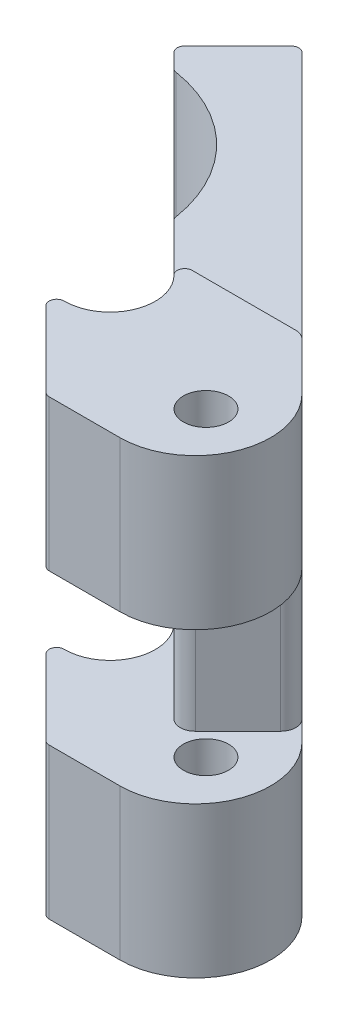
SolidWorks part; units mm, degrees
ref_plane "前视基准面" through (0, 0, 0) normal (0, 0, 1) x (1, 0, 0)
ref_plane "上视基准面" through (0, 0, 0) normal (0, 1, 0) x (1, 0, 0)
ref_plane "右视基准面" through (0, 0, 0) normal (1, 0, 0) x (0, 0, -1)
sketch "Sketch1" plane through (0, 0, 0) normal (0, 1, 0) x (1, 0, 0)
  line L0 (0, 0) -> (23.163, -23.163)
  line L1 (21.0416, -28.2843) -> (0, -28.2843)
  line L2 (0, 3.0516) -> (0, -30.2047) construction
  line L3 (4.2426, 4.2426) -> (34.234, -25.7487)
  line L4 (30.6985, -34.2843) -> (0, -34.2843)
  line L5 (0, 0) -> (4.2426, 4.2426)
  line L6 (0, -28.2843) -> (0, -34.2843)
  line L7 (4.2426, 4.2426) -> (42.7696, -34.2843) construction
  line L8 (42.7696, -34.2843) -> (0, -34.2843) construction
  line L9 (0, 0) -> (28.2843, -28.2843) construction
  line L10 (28.2843, -28.2843) -> (0, -28.2843) construction
  line L11 (21.0416, -25.2843) -> (30.6985, -29.2843) construction
  line L12 (30.6985, -29.2843) -> (46.0994, -35.6635) construction
  arc A0 (34.234, -25.7487) -> (30.6985, -34.2843) centre (30.6985, -29.2843) cw
  arc A1 (23.163, -23.163) -> (21.0416, -28.2843) centre (21.0416, -25.2843) cw
  circle A2 centre (31.9056, -29.7843) radius 1.6
  point P15 (28.2843, -28.2843)
  dimension "D4" = 5
  dimension "D5" = 3
  dimension "D6" = 3.2
  dimension "D1" = 40
  dimension "D2" = 45
  dimension "D7" = 4.5
  dimension "D3" = 6
extrude "Boss-Extrude1" add sketch "Sketch1" along normal blind 10
sketch "Sketch2" plane through (0, 10, 0) normal (0, 1, 0) x (1, 0, 0)
  line L1 (1.4142, -1.4142) -> (9.8995, -9.8995)
  line L2 (4.2426, 4.2426) -> (0, 0) construction
  line L3 (0, 0) -> (23.163, -23.163) construction
  line L5 (0, -28.2843) -> (0, -34.2843)
  line L11 (19.799, -28.2843) -> (25.799, -34.2843)
  line L12 (0, -28.2843) -> (19.799, -28.2843)
  line L13 (21.0416, -28.2843) -> (0, -28.2843) construction
  line L14 (0, -34.2843) -> (25.799, -34.2843)
  line L15 (0, -34.2843) -> (30.6985, -34.2843) construction
  line L16 (34.234, -25.7487) -> (4.2426, 4.2426) construction
  arc A1 (9.8995, -9.8995) -> (1.4142, -1.4142) centre (0, -11.3137) ccw
  dimension "D1" = 8
  dimension "D4" = 10
  dimension "D2" = 12
  dimension "D3" = 8
extrude "Cut-Extrude1" cut sketch "Sketch2" against normal through all
fillet "Fillet1" radius 0.5 6 edges at (25.799, 5, 34.2843) (19.799, 5, 28.2843) (1.4142, 5, 1.4142) (9.8995, 5, 9.8995) (0, 5, 0) (4.2426, 5, -4.2426)
sketch "Sketch3" plane through (0, 10, 0) normal (0, 1, 0) x (1, 0, 0)
  line L0 (20.6525, -29.1378) -> (25.6525, -34.1378)
  line L1 (26.0061, -34.2843) -> (30.6985, -34.2843)
  line L2 (22.2843, -22.2843) -> (30.3553, -22.2843)
  line L3 (31.0624, -22.5772) -> (34.234, -25.7487)
  line L4 (34.234, -25.7487) -> (4.5962, 3.8891) construction
  line L5 (22.2843, -22.2843) -> (23.163, -23.163)
  line L6 (10.0158, -10.0158) -> (23.163, -23.163) construction
  line L7 (21.0061, -28.2843) -> (21.0416, -28.2843)
  circle A2 centre (31.9056, -29.7843) radius 1.5
  arc A3 (21.0061, -28.2843) -> (20.6525, -29.1378) centre (21.0061, -28.7843) ccw
  arc A4 (25.6525, -34.1378) -> (26.0061, -34.2843) centre (26.0061, -33.7843) ccw
  arc A6 (30.3553, -22.2843) -> (31.0624, -22.5772) centre (30.3553, -23.2843) cw
  arc A7 (23.163, -23.163) -> (21.0416, -28.2843) centre (21.0416, -25.2843) cw
  arc A8 (21.0416, -28.2843) -> (23.163, -23.163) centre (21.0416, -25.2843) ccw construction
  arc A9 (30.6985, -34.2843) -> (34.234, -25.7487) centre (30.6985, -29.2843) ccw
  arc A10 (30.6985, -34.2843) -> (34.234, -25.7487) centre (30.6985, -29.2843) ccw construction
  dimension "D1" = 3
  dimension "D2" = 1.2426
  dimension "D3" = 1
  dimension "D4" = 1
  dimension "D5" = 1
extrude "Boss-Extrude2" add sketch "Sketch3" along normal blind 10 and the other way blind 20
sketch "Sketch4" plane through (0, 0, 0) normal (-0.7071, 0, 0.7071) x (0.7071, 0, 0.7071)
  line L0 (31.5147, 10) -> (41.5147, 10)
  line L1 (41.5147, 10) -> (41.5147, 0)
  line L2 (41.5147, 0) -> (31.5147, 0)
  line L3 (31.5147, 0) -> (31.5147, 10)
  dimension "D1" = 10
extrude "Cut-Extrude3" cut sketch "Sketch4" along normal through all
sketch "Sketch5" plane through (-4.2426, 0, 4.2426) normal (-0.7071, 0, 0.7071) x (0.7071, 0, 0.7071)
  line L4 (41.5147, 10) -> (50.1784, 10)
  line L5 (50.1784, 10) -> (50.1784, 0)
  line L6 (50.1784, 0) -> (41.5147, 0)
  line L7 (41.5147, 0) -> (41.5147, 10)
extrude "Cut-Extrude5" cut sketch "Sketch5" against normal through all
fillet "Fillet3" radius 0.5 2 edges at (22.2843, 15, 22.2843) (22.2843, -5, 22.2843)
fillet "Fillet4" radius 1 2 edges at (29.3553, 5, 29.3553) (33.598, 5, 25.1127)
